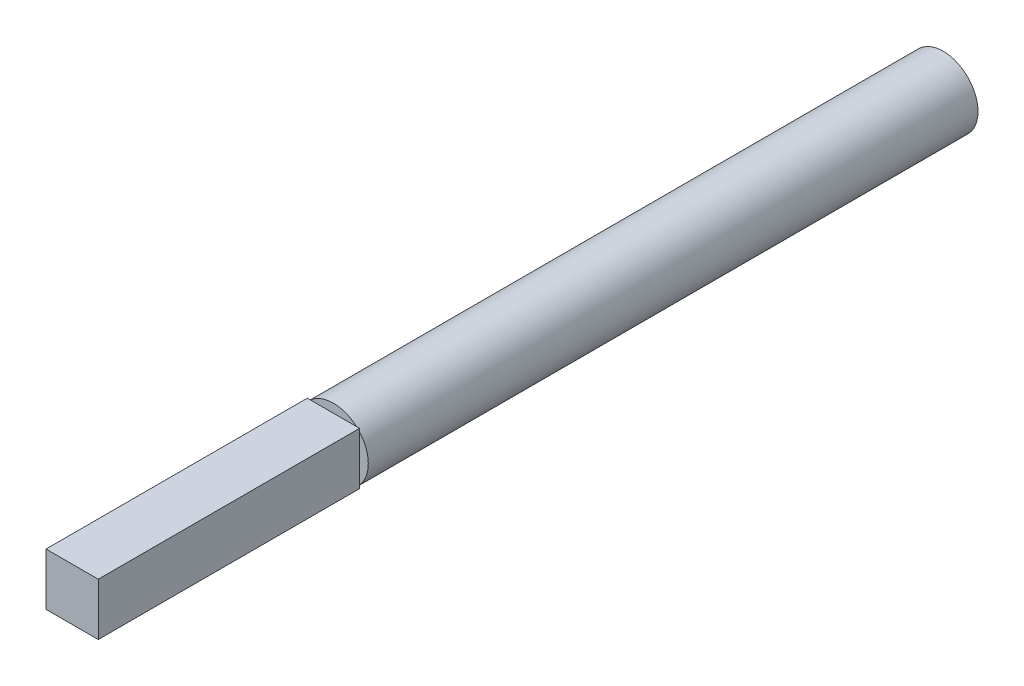
SolidWorks part; units mm, degrees
ref_plane "Front Plane" through (0, 0, 0) normal (0, 0, 1) x (1, 0, 0)
ref_plane "Top Plane" through (0, 0, 0) normal (0, 1, 0) x (1, 0, 0)
ref_plane "Right Plane" through (0, 0, 0) normal (1, 0, 0) x (0, 0, -1)
sketch "Sketch1" plane through (0, 0, 0) normal (0, 0, 1) x (1, 0, 0)
  circle A0 centre (0, 0) radius 5.08
  dimension "D1" = 10.16
extrude "Boss-Extrude1" add sketch "Sketch1" along normal blind 88.9
sketch "Sketch2" plane through (0, 0, 88.9) normal (0, 0, 1) x (1, 0, 0)
  line L1 (-3.81, 3.81) -> (3.81, 3.81)
  line L2 (-3.81, 3.81) -> (-3.81, -3.81)
  line L3 (-3.81, -3.81) -> (3.81, -3.81)
  line L4 (3.81, 3.81) -> (3.81, -3.81)
  line L5 (-3.81, 3.81) -> (3.81, -3.81) construction
  line L6 (-3.81, -3.81) -> (3.81, 3.81) construction
  point P0 (0, 0)
  dimension "D1" = 7.62
extrude "Boss-Extrude2" add sketch "Sketch2" along normal blind 38.1
